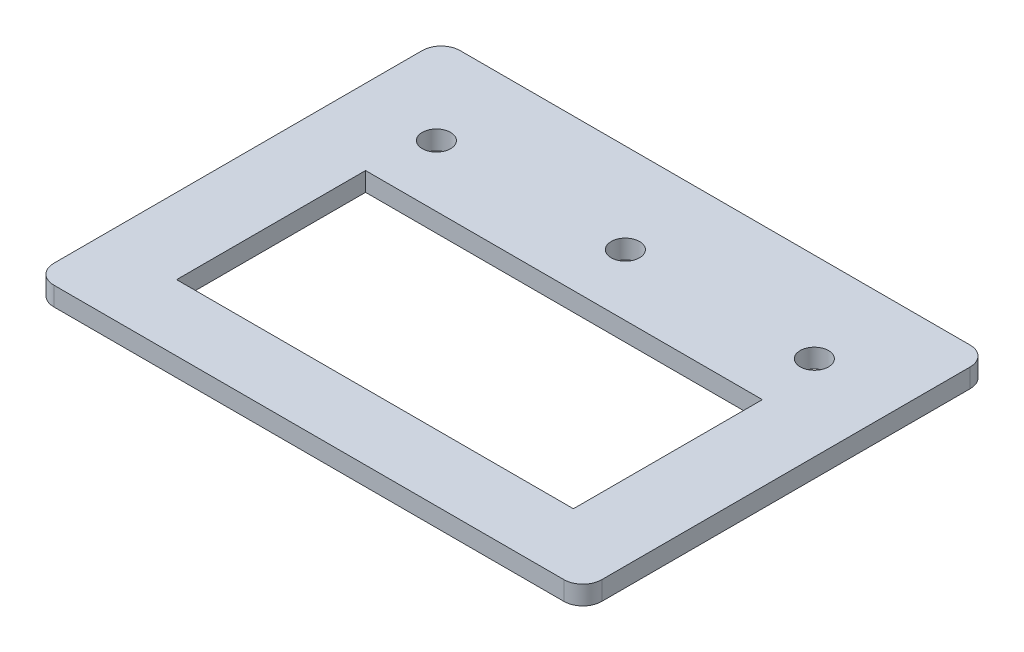
SolidWorks part; units mm, degrees
ref_plane "Front Plane" through (0, 0, 0) normal (0, 0, 1) x (1, 0, 0)
ref_plane "Top Plane" through (0, 0, 0) normal (0, 1, 0) x (1, 0, 0)
ref_plane "Right Plane" through (0, 0, 0) normal (1, 0, 0) x (0, 0, -1)
sketch "Sketch1" plane through (0, 0, 0) normal (0, 1, 0) x (1, 0, 0)
  line L0 (-29, -14.5) -> (29, -14.5) construction
  line L1 (-29, -21.5) -> (29, -21.5)
  line L2 (-29, -21.5) -> (-29, 21.5)
  line L3 (-29, 21.5) -> (29, 21.5)
  line L4 (29, -21.5) -> (29, 21.5)
  line L5 (-29, -21.5) -> (29, 21.5) construction
  line L6 (-29, 21.5) -> (29, -21.5) construction
  line L7 (0, -55) -> (0, 55) construction
  line L8 (-21, 5.5) -> (21, 5.5)
  line L9 (-21, 5.5) -> (-21, -14.5)
  line L10 (-21, -14.5) -> (21, -14.5)
  line L11 (21, 5.5) -> (21, -14.5)
  line L12 (-21, 5.5) -> (21, -14.5) construction
  line L13 (-21, -14.5) -> (21, 5.5) construction
  line L14 (0, 0) -> (0, 21.5) construction
  circle A0 centre (0, 12) radius 1.5
  circle A1 centre (20, 12) radius 1.5
  circle A2 centre (-20, 12) radius 1.5
  point P0 (0, 0)
  point P8 (0, -4.5)
  dimension "D6" = 3
  dimension "D8" = 20
  dimension "D9" = 12
  dimension "D1" = 58
  dimension "D2" = 43
  dimension "D3" = 7
  dimension "D4" = 42
  dimension "D5" = 20
  dimension "D7" = 20
extrude "Boss-Extrude1" add sketch "Sketch1" along normal blind 2
fillet "Fillet1" radius 2 4 edges at (-29, 1, -21.5) (29, 1, -21.5) (29, 1, 21.5) (-29, 1, 21.5)
